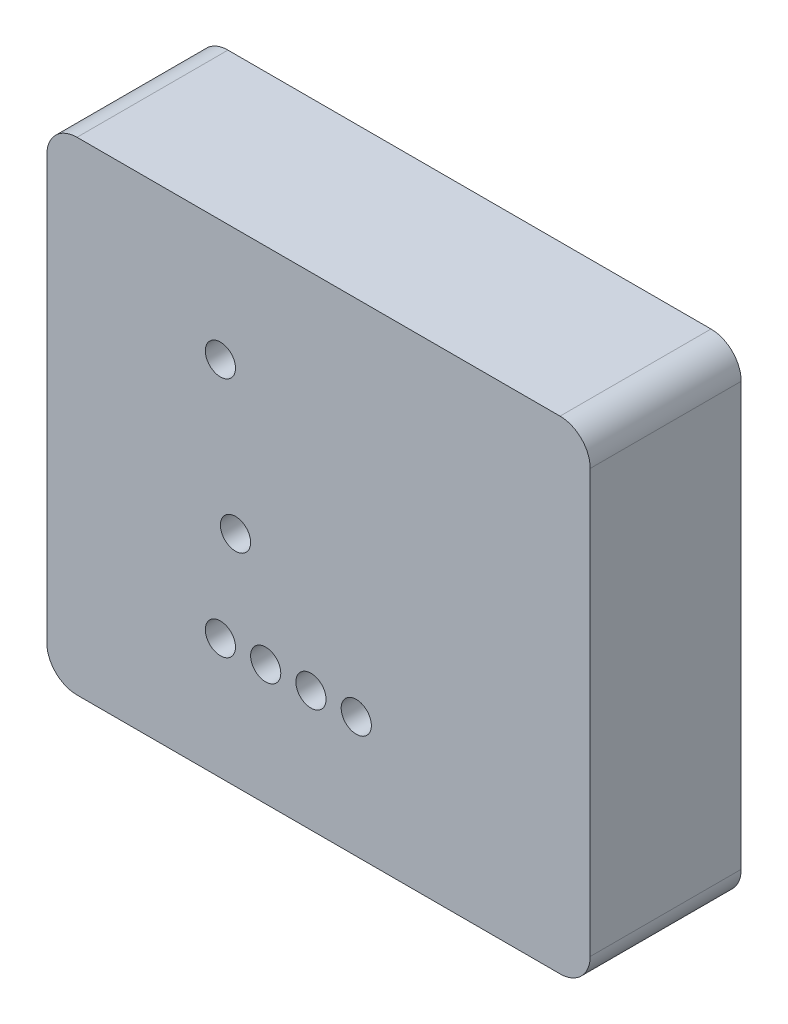
SolidWorks part; units mm, degrees
ref_plane "Front Plane" through (0, 0, 0) normal (0, 0, 1) x (1, 0, 0)
ref_plane "Top Plane" through (0, 0, 0) normal (0, 1, 0) x (1, 0, 0)
ref_plane "Right Plane" through (0, 0, 0) normal (1, 0, 0) x (0, 0, -1)
sketch "Sketch1" plane through (0, 0, 0) normal (0, 0, 1) x (1, 0, 0)
  line L0 (0, 0) -> (18, 0) construction
  line L1 (0, 0) -> (18, 0)
  line L2 (0, 0) -> (0, 16)
  line L3 (0, 16) -> (18, 16)
  line L4 (18, 0) -> (18, 16)
  circle A0 centre (5.75, 4) radius 0.5
  circle A1 centre (7.25, 4) radius 0.5
  circle A2 centre (8.75, 4) radius 0.5
  circle A3 centre (10.25, 4) radius 0.5
  circle A4 centre (5.75, 12) radius 0.5
  circle A5 centre (6.25, 7.25) radius 0.5
  dimension "D12" = 1
  dimension "D13" = 1
  dimension "D14" = 1
  dimension "D15" = 1
  dimension "D16" = 1
  dimension "D17" = 1
  dimension "D1" = 16
  dimension "D2" = 18
  dimension "D3" = 4
  dimension "D4" = 5.75
  dimension "D5" = 7.25
  dimension "D6" = 8.75
  dimension "D7" = 10.25
  dimension "D8" = 7.25
  dimension "D9" = 6.25
  dimension "D10" = 5.75
  dimension "D11" = 12
extrude "Boss-Extrude1" add sketch "Sketch1" along normal blind 5
fillet "Fillet2" radius 1 1 edges at (0, 0, 2.5)
fillet "Fillet3" radius 1 1 edges at (0, 16, 2.5)
fillet "Fillet4" radius 1 1 edges at (18, 16, 2.5)
fillet "Fillet5" radius 1 1 edges at (18, 0, 2.5)
